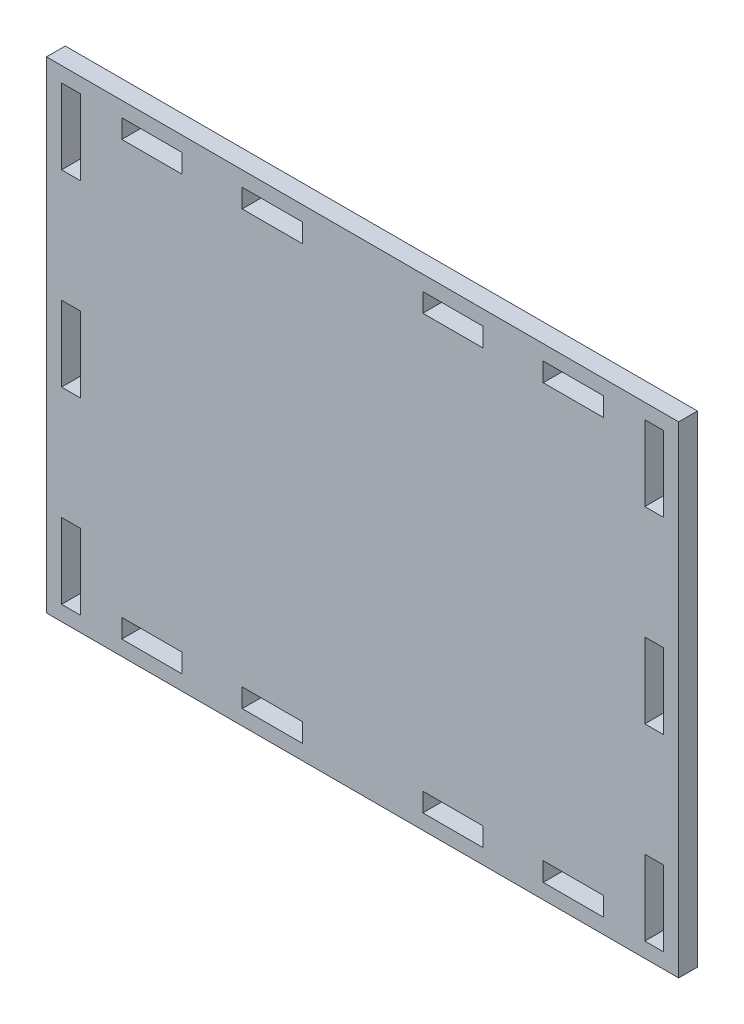
SolidWorks part; units mm, degrees
material "Beech"
ref_plane "Front" through (0, 0, 0) normal (0, 0, 1) x (1, 0, 0)
ref_plane "Top" through (0, 0, 0) normal (0, 1, 0) x (1, 0, 0)
ref_plane "Right" through (0, 0, 0) normal (1, 0, 0) x (0, 0, -1)
sketch "Sketch1" plane through (0, 0, 0) normal (0, 0, 1) x (1, 0, 0)
  line L0 (-42, 30) -> (0, 30) construction
  line L1 (0, 0) -> (-42, 0) construction
  line L2 (0, 0) -> (0, 32) construction
  line L3 (0, 32) -> (-42, 32) construction
  line L4 (-42, 0) -> (-42, 32) construction
  line L5 (0, 0) -> (-42, 32) construction
  line L6 (0, 32) -> (-42, 0) construction
  line L7 (0, 27.5) -> (-42, 27.5) construction
  line L8 (-16, 27.5) -> (-16, 30)
  line L9 (-32, 27.5) -> (-24, 27.5)
  line L10 (-32, 27.5) -> (-32, 30)
  line L11 (-32, 30) -> (-24, 30)
  line L12 (-24, 27.5) -> (-24, 30)
  line L13 (-32, 27.5) -> (-24, 30) construction
  line L14 (-32, 30) -> (-24, 27.5) construction
  line L15 (-16, 27.5) -> (-8, 27.5)
  line L16 (-8, 27.5) -> (-8, 30)
  line L17 (-16, 30) -> (-8, 30)
  line L18 (42, 32) -> (-42, 32)
  line L19 (-42, 32) -> (-42, -32)
  line L20 (42, -32) -> (-42, -32)
  line L21 (-16, -27.5) -> (-8, -27.5)
  line L22 (-8, -27.5) -> (-8, -30)
  line L23 (-16, -30) -> (-8, -30)
  line L24 (-16, -27.5) -> (-16, -30)
  line L25 (-32, -30) -> (-24, -30)
  line L26 (-24, -27.5) -> (-24, -30)
  line L27 (-32, -27.5) -> (-24, -27.5)
  line L28 (-32, -27.5) -> (-32, -30)
  line L29 (-40, 32) -> (-40, -32) construction
  line L30 (-37.5, -32) -> (-37.5, 32) construction
  line L31 (-40, 5) -> (-40, -5)
  line L32 (-40, 30) -> (-37.5, 30)
  line L33 (-40, 30) -> (-40, 20)
  line L34 (-40, 20) -> (-37.5, 20)
  line L35 (-37.5, 30) -> (-37.5, 20)
  line L36 (-40, 30) -> (-37.5, 20) construction
  line L37 (-40, 20) -> (-37.5, 30) construction
  line L38 (-40, 5) -> (-37.5, 5)
  line L39 (-37.5, 5) -> (-37.5, -5)
  line L40 (-40, -5) -> (-37.5, -5)
  line L41 (-40, -20) -> (-40, -30)
  line L42 (-40, -20) -> (-37.5, -20)
  line L43 (-37.5, -20) -> (-37.5, -30)
  line L44 (-40, -30) -> (-37.5, -30)
  line L45 (16, 27.5) -> (8, 27.5)
  line L46 (8, 27.5) -> (8, 30)
  line L47 (16, 30) -> (8, 30)
  line L48 (16, 27.5) -> (16, 30)
  line L49 (32, 30) -> (24, 30)
  line L50 (24, 27.5) -> (24, 30)
  line L51 (32, 27.5) -> (24, 27.5)
  line L52 (32, 27.5) -> (32, 30)
  line L53 (40, 20) -> (37.5, 20)
  line L54 (37.5, 30) -> (37.5, 20)
  line L55 (40, 30) -> (37.5, 30)
  line L56 (40, 30) -> (40, 20)
  line L57 (40, 5) -> (37.5, 5)
  line L58 (37.5, 5) -> (37.5, -5)
  line L59 (40, -5) -> (37.5, -5)
  line L60 (40, 5) -> (40, -5)
  line L61 (32, -27.5) -> (24, -27.5)
  line L62 (32, -27.5) -> (32, -30)
  line L63 (32, -30) -> (24, -30)
  line L64 (24, -27.5) -> (24, -30)
  line L65 (16, -27.5) -> (16, -30)
  line L66 (16, -30) -> (8, -30)
  line L67 (8, -27.5) -> (8, -30)
  line L68 (16, -27.5) -> (8, -27.5)
  line L69 (40, -20) -> (37.5, -20)
  line L70 (37.5, -20) -> (37.5, -30)
  line L71 (40, -30) -> (37.5, -30)
  line L72 (40, -20) -> (40, -30)
  line L73 (32, -27.5) -> (24, -27.5)
  line L74 (42, 32) -> (42, -32)
  point P4 (-21, 16)
  point P14 (-28, 28.75)
  point P37 (-38.75, 25)
  point P75 (0, -32)
  dimension "D1" = 42
  dimension "D2" = 32
  dimension "D3" = 2
  dimension "D4" = 2.5
  dimension "D5" = 8
  dimension "D6" = 10
  dimension "D8" = 8
  dimension "D9" = 2
  dimension "D10" = 2.5
  dimension "D11" = 10
  dimension "D12" = 3
  dimension "D13" = 15
  dimension "D7" = 2
extrude "Boss-Extrude1" add sketch "Sketch1" along normal blind 2.5 contours L74 L18 L19 L20 L68 L65 L66 L67 L64 L61 L62 L63 L52 L51 L50 L49 L48 L45 L46 L47 L44 L41 L42 L43 L40 L31 L38 L39 L28 L27 L26 L25 L24 L21 L22 L23 L12 L9 L10 L11 L8
